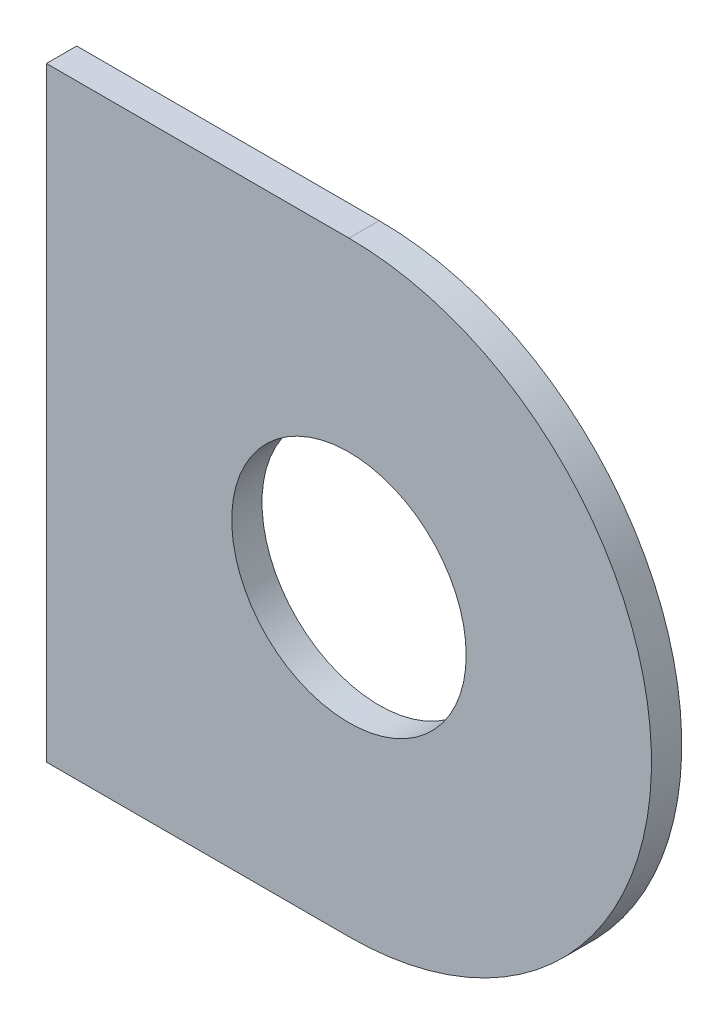
SolidWorks part; units mm, degrees
ref_plane "Face" through (0, 0, 0) normal (0, 0, 1) x (1, 0, 0)
ref_plane "Dessus" through (0, 0, 0) normal (0, 1, 0) x (1, 0, 0)
ref_plane "Droite" through (0, 0, 0) normal (1, 0, 0) x (0, 0, -1)
sketch "Esquisse1" plane through (0, 0, 0) normal (0, 0, 1) x (1, 0, 0)
  line L1 (0, 0) -> (20, 0)
  line L2 (0, 0) -> (0, 40)
  line L3 (0, 40) -> (20, 40)
  arc A0 (20, 0) -> (20, 40) centre (20, 20) ccw
  circle A1 centre (20, 20) radius 7.75
  dimension "D2" = 20
  dimension "D4" = 15.5
  dimension "D1" = 40
extrude "Boss.-Extru.1" add sketch "Esquisse1" along normal blind 2
